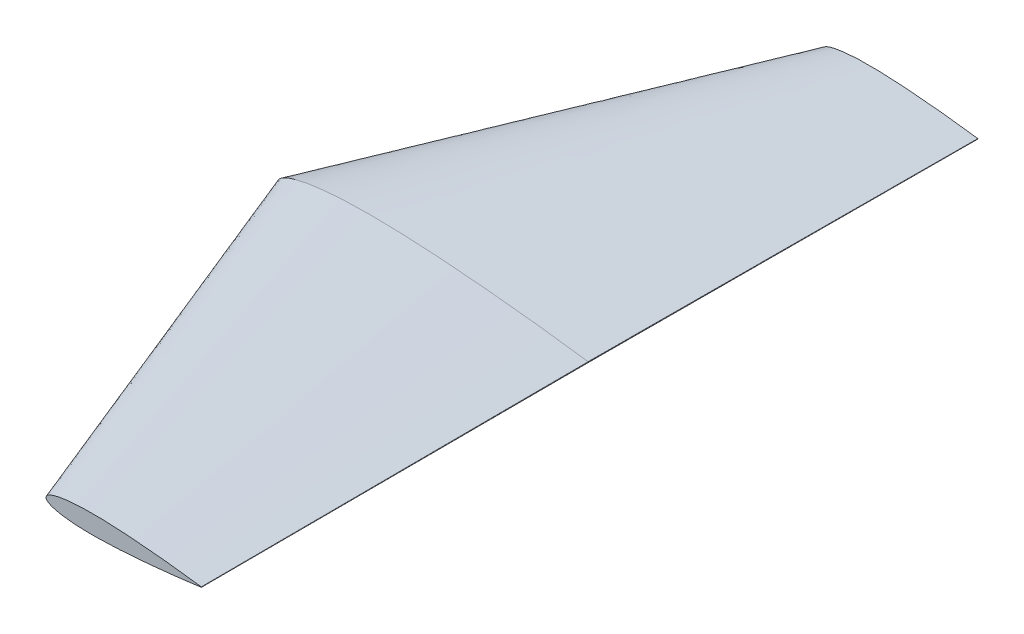
SolidWorks part; units mm, degrees
ref_plane "Front Plane" through (0, 0, 0) normal (0, 0, 1) x (1, 0, 0)
ref_plane "Top Plane" through (0, 0, 0) normal (0, 1, 0) x (1, 0, 0)
ref_plane "Right Plane" through (0, 0, 0) normal (1, 0, 0) x (0, 0, -1)
curve "Curve2"
  spline degree 3 poles (25.4, 0.032, 0) (25.3951, 0.0327, 0) (25.3753, 0.0355, 0) (25.3309, 0.0417, 0) (25.257, 0.052, 0) (25.1537, 0.0664, 0) (25.0214, 0.0846, 0) (24.8603, 0.1068, 0) (24.6708, 0.1326, 0) (24.4533, 0.1619, 0) (24.2084, 0.1946, 0) (23.9366, 0.2304, 0) (23.6385, 0.2691, 0) (23.3149, 0.3106, 0) (22.9666, 0.3545, 0) (22.5942, 0.4008, 0) (22.1987, 0.449, 0) (21.7811, 0.499, 0) (21.3422, 0.5505, 0) (20.8832, 0.6032, 0) (20.405, 0.6571, 0) (19.9089, 0.7116, 0) (19.3959, 0.7667, 0) (18.8673, 0.8219, 0) (18.3242, 0.8772, 0) (17.7681, 0.9321, 0) (17.2001, 0.9864, 0) (16.6216, 1.0399, 0) (16.0339, 1.0922, 0) (15.4384, 1.143, 0) (14.8366, 1.1921, 0) (14.2297, 1.2391, 0) (13.6193, 1.2836, 0) (13.0067, 1.3254, 0) (12.3935, 1.3642, 0) (11.7809, 1.3995, 0) (11.1705, 1.4311, 0) (10.5636, 1.4587, 0) (9.9618, 1.4818, 0) (9.3663, 1.5004, 0) (8.7786, 1.514, 0) (8.2001, 1.5224, 0) (7.632, 1.5254, 0) (7.0758, 1.5227, 0) (6.5327, 1.5144, 0) (6.0041, 1.5, 0) (5.491, 1.4798, 0) (4.9948, 1.4535, 0) (4.5166, 1.4212, 0) (4.0575, 1.3829, 0) (3.6185, 1.3388, 0) (3.2008, 1.2888, 0) (2.8052, 1.2334, 0) (2.4327, 1.1725, 0) (2.0841, 1.1064, 0) (1.7603, 1.0355, 0) (1.462, 0.96, 0) (1.1898, 0.8801, 0) (0.9445, 0.7962, 0) (0.7264, 0.7086, 0) (0.536, 0.6175, 0) (0.3737, 0.523, 0) (0.2396, 0.4254, 0) (0.1341, 0.3245, 0) (0.0574, 0.22, 0) (0.0105, 0.1114, 0) (-0.0051, 0, 0) (0.0105, -0.1114, 0) (0.0574, -0.22, 0) (0.1341, -0.3245, 0) (0.2396, -0.4254, 0) (0.3737, -0.523, 0) (0.536, -0.6175, 0) (0.7264, -0.7086, 0) (0.9445, -0.7962, 0) (1.1898, -0.8801, 0) (1.462, -0.96, 0) (1.7603, -1.0355, 0) (2.0841, -1.1064, 0) (2.4327, -1.1725, 0) (2.8052, -1.2334, 0) (3.2008, -1.2888, 0) (3.6185, -1.3388, 0) (4.0575, -1.3829, 0) (4.5166, -1.4212, 0) (4.9948, -1.4535, 0) (5.491, -1.4798, 0) (6.0041, -1.5, 0) (6.5327, -1.5144, 0) (7.0758, -1.5227, 0) (7.632, -1.5254, 0) (8.2001, -1.5224, 0) (8.7786, -1.514, 0) (9.3663, -1.5004, 0) (9.9618, -1.4818, 0) (10.5636, -1.4587, 0) (11.1705, -1.4311, 0) (11.7809, -1.3995, 0) (12.3935, -1.3642, 0) (13.0067, -1.3254, 0) (13.6193, -1.2836, 0) (14.2297, -1.2391, 0) (14.8366, -1.1921, 0) (15.4384, -1.143, 0) (16.0339, -1.0922, 0) (16.6216, -1.0399, 0) (17.2001, -0.9864, 0) (17.7681, -0.9321, 0) (18.3242, -0.8772, 0) (18.8673, -0.8219, 0) (19.3959, -0.7667, 0) (19.9089, -0.7116, 0) (20.405, -0.6571, 0) (20.8832, -0.6032, 0) (21.3422, -0.5505, 0) (21.7811, -0.499, 0) (22.1987, -0.449, 0) (22.5942, -0.4008, 0) (22.9666, -0.3545, 0) (23.3149, -0.3106, 0) (23.6385, -0.2691, 0) (23.9366, -0.2304, 0) (24.2084, -0.1946, 0) (24.4533, -0.1619, 0) (24.6708, -0.1326, 0) (24.8603, -0.1068, 0) (25.0214, -0.0846, 0) (25.1537, -0.0664, 0) (25.257, -0.052, 0) (25.3309, -0.0417, 0) (25.3753, -0.0355, 0) (25.3951, -0.0327, 0) (25.4, -0.032, 0) knots 0 0 0 0 0.000289 0.001156 0.002598 0.004612 0.007194 0.010336 0.014031 0.018272 0.023046 0.028343 0.03415 0.040454 0.047238 0.054489 0.062187 0.070314 0.078852 0.08778 0.097078 0.106722 0.116691 0.126961 0.137507 0.148306 0.159331 0.170556 0.181957 0.193504 0.205171 0.216932 0.228758 0.240621 0.252495 0.26435 0.276161 0.287898 0.299536 0.311047 0.322405 0.333584 0.344559 0.355306 0.3658 0.376018 0.385937 0.395538 0.404798 0.413699 0.422221 0.430349 0.438066 0.445357 0.452209 0.458612 0.464554 0.47003 0.475035 0.479569 0.483637 0.48725 0.490431 0.493219 0.495674 0.497891 0.5 0.502109 0.504326 0.506781 0.509569 0.51275 0.516363 0.520431 0.524965 0.52997 0.535446 0.541388 0.547791 0.554643 0.561934 0.569651 0.577779 0.586301 0.595202 0.604462 0.614063 0.623982 0.6342 0.644694 0.655441 0.666416 0.677595 0.688953 0.700464 0.712102 0.723839 0.73565 0.747505 0.759379 0.771242 0.783068 0.794829 0.806496 0.818043 0.829444 0.840669 0.851694 0.862493 0.873039 0.883309 0.893278 0.902922 0.91222 0.921148 0.929686 0.937813 0.945511 0.952762 0.959546 0.96585 0.971657 0.976954 0.981728 0.985969 0.989664 0.992806 0.995388 0.997402 0.998844 0.999711 1 1 1 1
sketch "Sketch1" plane through (0, 0, 0) normal (0, 0, 1) x (1, 0, 0)
  arc A0 (80.0329, 0.1008) -> (80.0329, -0.1008) centre (80, 0) cw
  spline S1 degree 3 poles (80.0329, 0.1008) (80.0173, 0.103) (79.955, 0.1118) (79.7065, 0.1465) (79.3346, 0.1985) (78.8398, 0.2667) (78.3322, 0.3365) (77.7351, 0.4178) (77.0499, 0.5101) (76.2781, 0.6131) (75.4217, 0.7259) (74.4827, 0.8481) (73.4631, 0.9786) (71.9499, 1.1696) (70.3376, 1.3678) (68.6301, 1.5722) (67.2473, 1.7345) (65.8008, 1.9007) (64.2942, 2.0703) (62.7309, 2.2421) (61.1145, 2.4157) (59.4489, 2.5897) (57.7378, 2.7639) (55.9854, 2.9369) (54.1957, 3.1082) (52.3729, 3.2766) (50.5212, 3.4415) (48.645, 3.6016) (46.7486, 3.7562) (44.8364, 3.9042) (42.9131, 4.0446) (40.9829, 4.1763) (39.0506, 4.2984) (36.483, 4.4465) (33.9269, 4.5714) (30.7711, 4.6929) (28.2866, 4.7613) (25.8376, 4.7969) (24.0477, 4.8063) (22.2952, 4.798) (20.584, 4.7717) (18.9183, 4.7265) (17.3017, 4.6627) (15.7382, 4.5798) (14.2314, 4.4781) (12.7847, 4.3575) (11.4016, 4.2183) (10.0853, 4.061) (8.8389, 3.8862) (7.6651, 3.6944) (6.5669, 3.4863) (5.5466, 3.2629) (4.6066, 3.0248) (3.7491, 2.7732) (2.9759, 2.5089) (2.2887, 2.2327) (1.6888, 1.9455) (1.1774, 1.6479) (0.755, 1.3404) (0.4226, 1.0225) (0.1808, 0.6933) (0.033, 0.3511) (-0.0161, 0) (0.033, -0.3511) (0.1808, -0.6933) (0.4226, -1.0225) (0.755, -1.3404) (1.1774, -1.6479) (1.6888, -1.9455) (2.2887, -2.2327) (2.9759, -2.5089) (3.7491, -2.7732) (4.6066, -3.0248) (5.5466, -3.2629) (6.5669, -3.4863) (7.6651, -3.6944) (8.8389, -3.8862) (10.0853, -4.061) (11.4016, -4.2183) (12.7847, -4.3575) (14.2314, -4.4781) (15.7382, -4.5798) (17.3017, -4.6627) (18.9183, -4.7265) (20.584, -4.7717) (22.2952, -4.798) (24.0477, -4.8063) (25.8376, -4.7969) (28.2866, -4.7613) (31.4094, -4.6753) (34.5648, -4.542) (37.1204, -4.4097) (39.0506, -4.2984) (40.9829, -4.1763) (42.9131, -4.0446) (44.8364, -3.9042) (46.7486, -3.7562) (48.645, -3.6016) (50.5212, -3.4415) (52.3729, -3.2766) (54.1957, -3.1082) (55.9854, -2.9369) (57.7378, -2.7639) (59.4489, -2.5897) (61.1145, -2.4157) (62.7309, -2.2421) (64.2942, -2.0703) (65.8008, -1.9007) (67.2473, -1.7345) (68.6301, -1.5722) (70.3376, -1.3678) (71.9499, -1.1696) (73.4631, -0.9786) (74.4827, -0.8481) (75.4217, -0.7259) (76.2781, -0.6131) (77.0499, -0.5101) (77.7351, -0.4178) (78.3322, -0.3365) (78.8398, -0.2667) (79.3346, -0.1985) (79.7065, -0.1465) (79.955, -0.1118) (80.0173, -0.103) (80.0329, -0.1008) knots 0 0 0 0 0.000289 0.001156 0.004612 0.007194 0.010336 0.014031 0.018272 0.023046 0.028343 0.03415 0.040454 0.047238 0.062187 0.070314 0.078852 0.08778 0.097078 0.106722 0.116691 0.126961 0.137507 0.148306 0.159331 0.170556 0.181957 0.193504 0.205171 0.216932 0.228758 0.240621 0.252495 0.26435 0.287898 0.299536 0.322405 0.333584 0.344559 0.355306 0.3658 0.376018 0.385937 0.395538 0.404798 0.413699 0.422221 0.430349 0.438066 0.445357 0.452209 0.458612 0.464554 0.47003 0.475035 0.479569 0.483637 0.48725 0.490431 0.493219 0.495674 0.497891 0.5 0.502109 0.504326 0.506781 0.509569 0.51275 0.516363 0.520431 0.524965 0.52997 0.535446 0.541388 0.547791 0.554643 0.561934 0.569651 0.577779 0.586301 0.595202 0.604462 0.614063 0.623982 0.6342 0.644694 0.655441 0.666416 0.677595 0.700464 0.723839 0.73565 0.747505 0.759379 0.771242 0.783068 0.794829 0.806496 0.818043 0.829444 0.840669 0.851694 0.862493 0.873039 0.883309 0.893278 0.902922 0.91222 0.921148 0.929686 0.937813 0.952762 0.959546 0.96585 0.971657 0.976954 0.981728 0.985969 0.989664 0.992806 0.995388 0.998844 0.999711 1 1 1 1
ref_plane "Plane1" through (0, 0, 100) normal (0, 0, 1) x (1, 0, 0)
sketch "Sketch2" plane through (0, 0, 100) normal (0, 0, 1) x (1, 0, 0)
  arc A0 (80.4, 0.0504) -> (80.4, -0.0504) centre (80.4, 0) cw
  spline S1 degree 3 poles (80.4, 0.0504) (80.3922, 0.0515) (80.3611, 0.0559) (80.2369, 0.0732) (80.051, 0.0992) (79.8037, 0.1333) (79.55, 0.1682) (79.2516, 0.2088) (78.9091, 0.255) (78.5234, 0.3064) (78.0954, 0.3628) (77.626, 0.4239) (77.1164, 0.4891) (76.3602, 0.5845) (75.5544, 0.6836) (74.7009, 0.7858) (74.0098, 0.8669) (73.2869, 0.95) (72.5339, 1.0347) (71.7526, 1.1206) (70.9447, 1.2073) (70.1122, 1.2943) (69.2571, 1.3814) (68.3812, 1.4678) (67.4867, 1.5534) (66.5757, 1.6376) (65.6502, 1.72) (64.7125, 1.8001) (63.7647, 1.8773) (62.809, 1.9513) (61.8477, 2.0215) (60.8831, 2.0873) (59.9173, 2.1483) (58.634, 2.2223) (57.3565, 2.2847) (55.7792, 2.3455) (54.5375, 2.3797) (53.3135, 2.3975) (52.4189, 2.4022) (51.543, 2.398) (50.6878, 2.3848) (49.8552, 2.3623) (49.0473, 2.3304) (48.2659, 2.289) (47.5128, 2.2381) (46.7897, 2.1778) (46.0985, 2.1083) (45.4406, 2.0297) (44.8176, 1.9423) (44.231, 1.8464) (43.6821, 1.7424) (43.1721, 1.6308) (42.7024, 1.5118) (42.2738, 1.386) (41.8873, 1.2539) (41.5439, 1.1159) (41.244, 0.9724) (40.9884, 0.8236) (40.7774, 0.6699) (40.6112, 0.511) (40.4904, 0.3465) (40.4165, 0.1755) (40.392, 0) (40.4165, -0.1755) (40.4904, -0.3465) (40.6112, -0.511) (40.7774, -0.6699) (40.9884, -0.8236) (41.244, -0.9724) (41.5439, -1.1159) (41.8873, -1.2539) (42.2738, -1.386) (42.7024, -1.5118) (43.1721, -1.6308) (43.6821, -1.7424) (44.231, -1.8464) (44.8176, -1.9423) (45.4406, -2.0297) (46.0985, -2.1083) (46.7897, -2.1778) (47.5128, -2.2381) (48.2659, -2.289) (49.0473, -2.3304) (49.8552, -2.3623) (50.6878, -2.3848) (51.543, -2.398) (52.4189, -2.4022) (53.3135, -2.3975) (54.5375, -2.3797) (56.0982, -2.3367) (57.6753, -2.2701) (58.9526, -2.204) (59.9173, -2.1483) (60.8831, -2.0873) (61.8477, -2.0215) (62.809, -1.9513) (63.7647, -1.8773) (64.7125, -1.8001) (65.6502, -1.72) (66.5757, -1.6376) (67.4867, -1.5534) (68.3812, -1.4678) (69.2571, -1.3814) (70.1122, -1.2943) (70.9447, -1.2073) (71.7526, -1.1206) (72.5339, -1.0347) (73.2869, -0.95) (74.0098, -0.8669) (74.7009, -0.7858) (75.5544, -0.6836) (76.3602, -0.5845) (77.1164, -0.4891) (77.626, -0.4239) (78.0954, -0.3628) (78.5234, -0.3064) (78.9091, -0.255) (79.2516, -0.2088) (79.55, -0.1682) (79.8037, -0.1333) (80.051, -0.0992) (80.2369, -0.0732) (80.3611, -0.0559) (80.3922, -0.0515) (80.4, -0.0504) knots 0 0 0 0 0.000289 0.001156 0.004612 0.007194 0.010336 0.014031 0.018272 0.023046 0.028343 0.03415 0.040454 0.047238 0.062187 0.070314 0.078852 0.08778 0.097078 0.106722 0.116691 0.126961 0.137507 0.148306 0.159331 0.170556 0.181957 0.193504 0.205171 0.216932 0.228758 0.240621 0.252495 0.26435 0.287898 0.299536 0.322405 0.333584 0.344559 0.355306 0.3658 0.376018 0.385937 0.395538 0.404798 0.413699 0.422221 0.430349 0.438066 0.445357 0.452209 0.458612 0.464554 0.47003 0.475035 0.479569 0.483637 0.48725 0.490431 0.493219 0.495674 0.497891 0.5 0.502109 0.504326 0.506781 0.509569 0.51275 0.516363 0.520431 0.524965 0.52997 0.535446 0.541388 0.547791 0.554643 0.561934 0.569651 0.577779 0.586301 0.595202 0.604462 0.614063 0.623982 0.6342 0.644694 0.655441 0.666416 0.677595 0.700464 0.723839 0.73565 0.747505 0.759379 0.771242 0.783068 0.794829 0.806496 0.818043 0.829444 0.840669 0.851694 0.862493 0.873039 0.883309 0.893278 0.902922 0.91222 0.921148 0.929686 0.937813 0.952762 0.959546 0.96585 0.971657 0.976954 0.981728 0.985969 0.989664 0.992806 0.995388 0.998844 0.999711 1 1 1 1
  point P0 (40.4, 0)
  point P4 (40.4, 0)
  dimension "D1" = 40.4
loft "Loft1" add profiles "Sketch1", "Sketch2"
mirror "Mirror1" about plane through (0, 0, 0) normal (0, 0, -1) of "Loft1"
